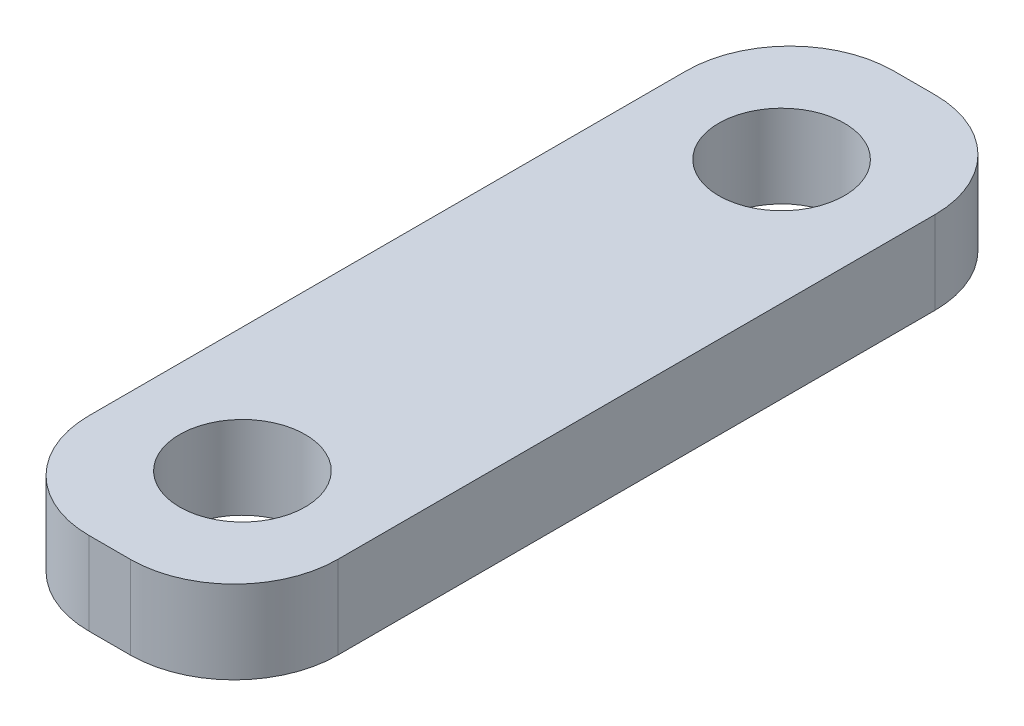
SolidWorks part; units mm, degrees
ref_plane "前视基准面" through (0, 0, 0) normal (0, 0, 1) x (1, 0, 0)
ref_plane "上视基准面" through (0, 0, 0) normal (0, 1, 0) x (1, 0, 0)
ref_plane "右视基准面" through (0, 0, 0) normal (1, 0, 0) x (0, 0, -1)
other "Configuration Table"
sketch "草图1" plane through (0, 0, 0) normal (0, 1, 0) x (1, 0, 0)
  line L0 (3, 19.4) -> (3, 0) construction
  line L1 (0, 0) -> (6, 0)
  line L2 (0, 0) -> (0, 19.4)
  line L3 (0, 19.4) -> (6, 19.4)
  line L4 (6, 0) -> (6, 19.4)
  line L5 (0, 9.7) -> (6, 9.7) construction
  circle A0 centre (3, 16.2) radius 1.515
  circle A1 centre (3, 3.2) radius 1.515
  dimension "D3" = 3.03
  dimension "D4" = 3.2
  dimension "D1" = 6
  dimension "D2" = 13
extrude "凸台-拉伸1" add sketch "草图1" along normal blind 2
fillet "圆角1" radius 2.5 4 edges at (6, 1, 0) (0, 1, 0) (6, 1, -19.4) (0, 1, -19.4)
